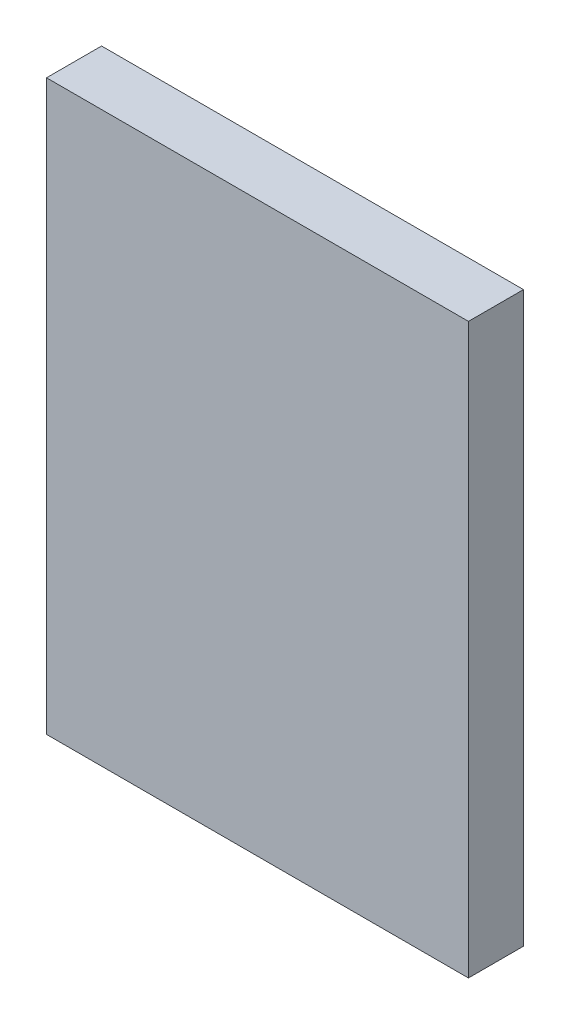
SolidWorks part; units mm, degrees
ref_plane "Přední rovina" through (0, 0, 0) normal (0, 0, 1) x (1, 0, 0)
ref_plane "Horní rovina" through (0, 0, 0) normal (0, 1, 0) x (1, 0, 0)
ref_plane "Pravá rovina" through (0, 0, 0) normal (1, 0, 0) x (0, 0, -1)
sketch "Skica1" plane through (0, 0, 0) normal (0, 0, 1) x (1, 0, 0)
  line L1 (5.75, -7.75) -> (-5.75, -7.75)
  line L2 (5.75, -7.75) -> (5.75, 7.75)
  line L3 (5.75, 7.75) -> (-5.75, 7.75)
  line L4 (-5.75, -7.75) -> (-5.75, 7.75)
  line L5 (5.75, -7.75) -> (-5.75, 7.75) construction
  line L6 (5.75, 7.75) -> (-5.75, -7.75) construction
  point P0 (0, 0)
  dimension "D1" = 11.5
  dimension "D2" = 15.5
extrude "Přidat vysunutím2" add sketch "Skica1" along normal blind 1.5 contours L3 L4 L1 L2
